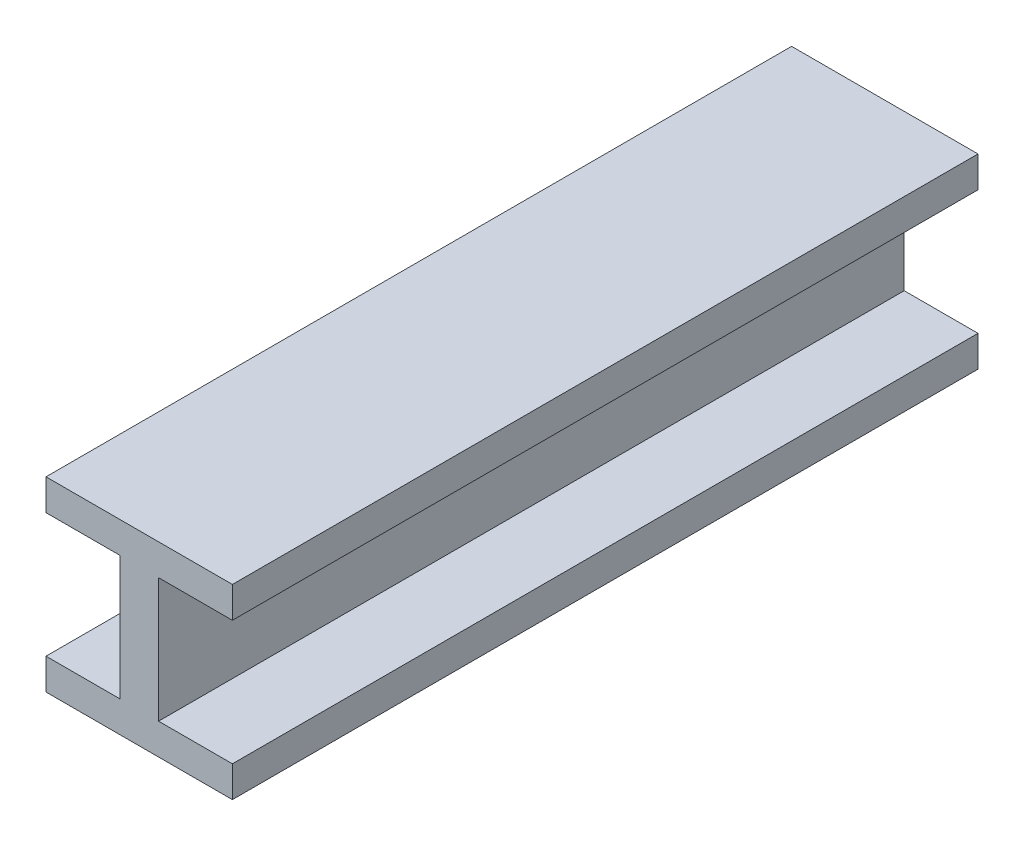
SolidWorks part; units mm, degrees
ref_plane "Front Plane" through (0, 0, 0) normal (0, 0, 1) x (1, 0, 0)
ref_plane "Top Plane" through (0, 0, 0) normal (0, 1, 0) x (1, 0, 0)
ref_plane "Right Plane" through (0, 0, 0) normal (1, 0, 0) x (0, 0, -1)
sketch "Sketch1" plane through (0, 0, 0) normal (0, 0, 1) x (1, 0, 0)
  line L0 (0, 50.8) -> (0, -50.8) construction
  line L1 (3.9688, 12.7) -> (3.9688, -12.7)
  line L2 (-3.9687, 12.7) -> (-3.9687, -12.7)
  line L3 (3.9688, -12.7) -> (19.05, -12.7)
  line L4 (-3.9687, -12.7) -> (-19.05, -12.7)
  line L5 (19.05, -12.7) -> (19.05, -19.05)
  line L6 (-19.05, -12.7) -> (-19.05, -19.05)
  line L7 (19.05, -19.05) -> (-19.05, -19.05)
  line L8 (-3.9687, 0) -> (3.9688, 0) construction
  line L9 (-19.05, 12.7) -> (-19.05, 19.05)
  line L10 (-3.9687, 12.7) -> (-19.05, 12.7)
  line L11 (19.05, 19.05) -> (-19.05, 19.05)
  line L12 (19.05, 12.7) -> (19.05, 19.05)
  line L13 (3.9688, 12.7) -> (19.05, 12.7)
  point P4 (0, 0)
  point P7 (3.9688, 0)
  point P13 (0, -19.05)
  point P17 (0, 0)
  dimension "D1" = 6.35
  dimension "D2" = 38.1
  dimension "D3" = 7.9375
  dimension "D4" = 38.1
extrude "Boss-Extrude2" add sketch "Sketch1" along normal mid plane 152.4
equation "\"T\"= .25"
equation "\"H\"= 1.5"
equation "\"W\"= 1.5"
equation "\"D3@Sketch1\"=\"T\"*1.25"
equation "\"D1@Sketch1\"=\"T\""
equation "\"D4@Sketch1\"=\"W\""
equation "\"D2@Sketch1\"=\"H\""
